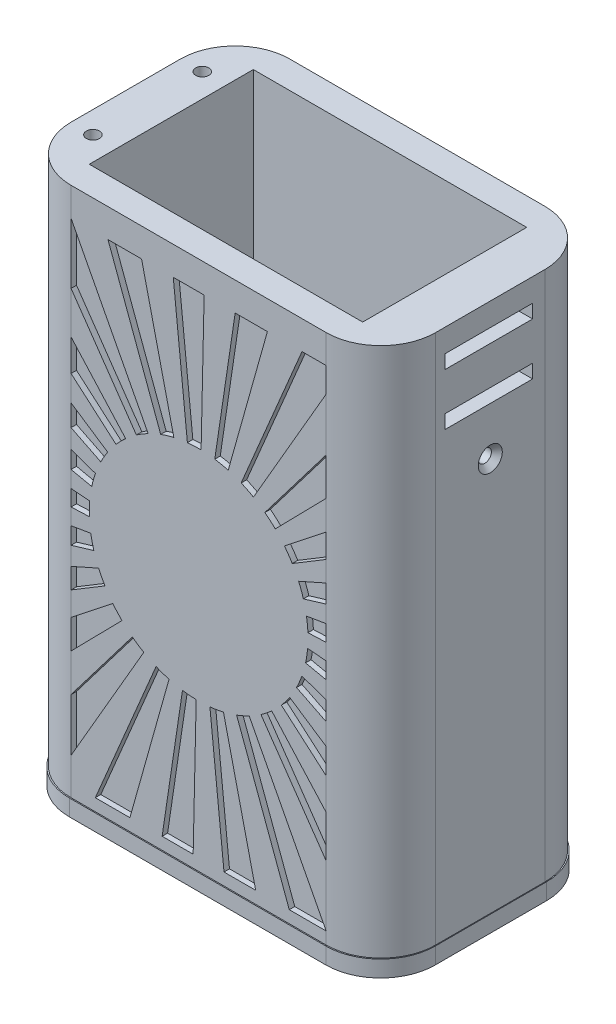
SolidWorks part; units mm, degrees
ref_plane "Front Plane" through (0, 0, 0) normal (0, 0, 1) x (1, 0, 0)
ref_plane "Top Plane" through (0, 0, 0) normal (0, 1, 0) x (1, 0, 0)
ref_plane "Right Plane" through (0, 0, 0) normal (1, 0, 0) x (0, 0, -1)
sketch "Sketch4" plane through (0, 0, 0) normal (0, 1, 0) x (1, 0, 0)
  line L1 (23.3333, 20) -> (-23.3333, 20)
  line L2 (33.3333, 10) -> (33.3333, -10)
  line L3 (23.3333, -20) -> (-23.3333, -20)
  line L4 (-33.3333, 10) -> (-33.3333, -10)
  line L5 (33.3333, 20) -> (-33.3333, -20) construction
  line L6 (33.3333, -20) -> (-33.3333, 20) construction
  line L7 (25, 15) -> (-25, 15)
  line L8 (25, 15) -> (25, -15)
  line L9 (25, -15) -> (-25, -15)
  line L10 (-25, 15) -> (-25, -15)
  line L11 (25, 15) -> (-25, -15) construction
  line L12 (25, -15) -> (-25, 15) construction
  arc A0 (23.3333, 20) -> (33.3333, 10) centre (23.3333, 10) cw
  arc A1 (-23.3333, -20) -> (-33.3333, -10) centre (-23.3333, -10) cw
  arc A2 (33.3333, -10) -> (23.3333, -20) centre (23.3333, -10) cw
  arc A3 (-23.3333, 20) -> (-33.3333, 10) centre (-23.3333, 10) ccw
  point P0 (0, 0)
  point P18 (0, 0)
  dimension "D1" = 10
extrude "Boss-Extrude1" add sketch "Sketch4" along normal blind 100
sketch "Sketch6" plane through (0, 0, 20) normal (0, 0, 1) x (1, 0, 0)
  line L0 (0, -22) -> (0, 22) construction
  line L1 (-23.3333, 94.7801) -> (23.3333, 94.7801)
  line L2 (-23.3333, 94.7801) -> (-23.3333, 5.2199)
  line L3 (-23.3333, 5.2199) -> (23.3333, 5.2199)
  line L4 (23.3333, 94.7801) -> (23.3333, 5.2199)
  line L5 (-23.3333, 94.7801) -> (-9.2335, 67.7204) construction
  line L6 (-23.3333, 5.2199) -> (-9.2498, 32.2482) construction
  line L7 (23.3333, 100) -> (23.3333, 0) construction
  line L8 (22, 0) -> (-22, 0) construction
  line L9 (-9.2335, 67.7204) -> (-23.3333, 94.7801)
  line L10 (0.0013, 49.9999) -> (0.0007, 50.0014)
  line L11 (0.0025, 49.9997) -> (0.0017, 50.0032)
  line L12 (0.0037, 49.9993) -> (0.003, 50.0058)
  line L13 (0.0048, 49.9988) -> (0.0051, 50.0097)
  line L14 (0.0059, 49.9981) -> (0.0086, 50.0166)
  line L15 (0.0068, 49.9973) -> (0.0165, 50.0316)
  line L16 (0.0077, 49.9964) -> (0.0486, 50.0932)
  line L17 (10.0235, 67.2878) -> (23.3333, 90.2692)
  line L18 (12.1129, 65.8957) -> (23.3333, 80.6366)
  line L19 (14.0116, 64.2528) -> (23.3333, 73.7462)
  line L20 (15.6895, 62.3849) -> (23.3333, 68.4265)
  line L21 (17.1202, 60.3213) -> (23.3333, 64.0726)
  line L22 (18.2811, 58.0946) -> (23.3333, 60.3358)
  line L23 (19.1539, 55.7398) -> (23.3333, 56.9955)
  line L24 (19.7248, 53.294) -> (23.3333, 53.8994)
  line L25 (19.9846, 50.7959) -> (23.3333, 50.9317)
  line L26 (19.9293, 48.2847) -> (23.3333, 47.9942)
  line L27 (0.0077, 49.9836) -> (0.0086, 49.9834)
  line L28 (0.0068, 49.9827) -> (0.0095, 49.9818)
  line L29 (0.0059, 49.9819) -> (0.0107, 49.9795)
  line L30 (0.0048, 49.9812) -> (0.0124, 49.9762)
  line L31 (0.0037, 49.9807) -> (0.0153, 49.9707)
  line L32 (-0.0525, 50.0416) -> (0.021, 49.9597)
  line L33 (0.0013, 49.9801) -> (0.038, 49.927)
  line L34 (9.2422, 32.2429) -> (23.3333, 5.1999)
  line L35 (6.9451, 31.2242) -> (16.576, 5.2199)
  line L36 (4.5384, 30.5015) -> (10.4321, 5.2199)
  line L37 (2.0601, 30.0863) -> (4.6396, 5.2199)
  line L38 (-0.4508, 29.9852) -> (-1.0031, 5.2199)
  line L39 (-2.9544, 30.1997) -> (-6.6777, 5.2199)
  line L40 (-5.4114, 30.7264) -> (-12.5702, 5.2199)
  line L41 (-7.7829, 31.5571) -> (-18.896, 5.2199)
  line L42 (-10.0314, 32.6785) -> (-23.3333, 9.7108)
  line L43 (-12.1215, 34.0729) -> (-23.3333, 19.3434)
  line L44 (-14.0202, 35.7183) -> (-23.3333, 26.2338)
  line L45 (-15.6976, 37.5887) -> (-23.3333, 31.5535)
  line L46 (-17.1272, 39.6545) -> (-23.3333, 35.9074)
  line L47 (-18.2864, 41.8831) -> (-23.3333, 39.6442)
  line L48 (-19.1571, 44.2392) -> (-23.3333, 42.9845)
  line L49 (-19.7256, 46.6858) -> (-23.3333, 46.0806)
  line L50 (-0.009, 49.9943) -> (-0.01, 49.9942)
  line L51 (-0.0084, 49.9954) -> (-0.0112, 49.9956)
  line L52 (-0.0077, 49.9964) -> (-0.0129, 49.9975)
  line L53 (-0.0068, 49.9973) -> (-0.0155, 50.0003)
  line L54 (-0.0059, 49.9981) -> (-0.0196, 50.0049)
  line L55 (-0.0048, 49.9988) -> (-0.0279, 50.0141)
  line L56 (-0.0037, 49.9993) -> (-0.0525, 50.0416)
  line L57 (-13.3535, 64.868) -> (-23.3333, 75.9819)
  line L58 (-11.3832, 66.4238) -> (-23.3333, 83.6676)
  line L59 (-23.3333, 94.7801) -> (-23.3333, 5.2199)
  line L60 (23.3333, 94.7801) -> (23.3333, 5.2199)
  line L61 (9.2503, 32.2472) -> (23.3333, 5.2199) construction
  line L62 (-0.0056, 49.9893) -> (0.0486, 50.0932) construction
  line L63 (-19.9829, 49.1842) -> (-23.3333, 49.0483)
  line L64 (-19.9251, 51.695) -> (-23.3333, 51.9858)
  line L65 (-19.5531, 54.1785) -> (-23.3333, 54.9874)
  line L66 (-18.8729, 56.5958) -> (-23.3333, 58.1559)
  line L67 (-17.8952, 58.9086) -> (-23.3333, 61.6173)
  line L68 (-16.6354, 61.0806) -> (-23.3333, 65.5438)
  line L69 (-15.1135, 63.0775) -> (-23.3333, 70.1921)
  line L70 (0, 50) -> (0.038, 49.927) construction
  line L71 (-6.9383, 68.7375) -> (-16.5834, 94.7801)
  line L72 (-4.5339, 69.4591) -> (-10.4367, 94.7801)
  line L73 (-2.058, 69.8738) -> (-4.6417, 94.7801)
  line L74 (0.4503, 69.975) -> (1.0035, 94.7801)
  line L75 (2.9516, 69.7613) -> (6.6807, 94.7801)
  line L76 (5.4064, 69.2358) -> (12.5758, 94.7801)
  line L77 (7.7762, 68.407) -> (18.9044, 94.7801)
  line L78 (9.234, 67.7214) -> (23.3333, 94.7801) construction
  line L79 (19.5596, 45.8001) -> (23.3333, 44.9926)
  line L80 (18.8813, 43.3813) -> (23.3333, 41.8241)
  line L81 (17.9051, 41.0664) -> (23.3333, 38.3627)
  line L82 (16.6463, 38.8922) -> (23.3333, 34.4362)
  line L83 (15.1248, 36.8927) -> (23.3333, 29.7879)
  line L84 (13.3645, 35.0998) -> (23.3333, 23.9981)
  line L85 (11.3933, 33.5417) -> (23.3333, 16.3124)
  circle A0 centre (0.0013, 49.9801) radius 20
  point P0 (0, 50)
  dimension "D1" = 50
  dimension "D2" = 50
hole_wizard "CSK for M2 Countersunk Flat Head Screw1" positions "Sketch8" profile "Sketch7" countersink size "M2" standard "ISO"
sketch "Sketch8" plane through (33.3333, 0, 0) normal (1, 0, 0) x (0, 0, -1)
  line L0 (-10, 100) -> (10, 100) construction
  point P1 (0, 75)
  dimension "D1" = 25
sketch "Sketch7" plane through (33.3333, 75, 0) normal (0, 1, 0) x (0, 0, -1)
  line L0 (0, 0) -> (0, 20.721)
  line L1 (0, 20.721) -> (1.2, 20)
  line L2 (1.2, 20) -> (1.2, 1)
  line L3 (1.2, 1) -> (2.2, 0)
  line L5 (2.2, 0) -> (0, 0)
  line L6 (-1.2, 1) -> (-2.2, 0) construction
  line L10 (0, 20.721) -> (-1.2, 20) construction
  line L11 (0, -6.35) -> (0, 107.95) construction
  dimension "Hole Dia." = 2.4
  dimension "Hole Depth" = 20
  dimension "Near C'Sink Dia." = 4.4
  dimension "Near C'Sink Angle" = 90
  dimension "Drill Angle" = 118
sketch "Sketch9" plane through (33.3333, 0, 0) normal (1, 0, 0) x (0, 0, -1)
  line L0 (-8.256, 93.2854) -> (7.744, 93.2854)
  line L1 (-8.256, 95.7854) -> (7.744, 95.7854)
  line L2 (-8.256, 95.7854) -> (-8.256, 93.2854)
  line L3 (-8.256, 83.7854) -> (7.744, 83.7854)
  line L4 (7.744, 95.7854) -> (7.744, 93.2854)
  line L5 (-8.256, 95.7854) -> (-4.9227, 93.2854) construction
  line L6 (-8.256, 83.7854) -> (-4.9227, 86.2854) construction
  line L7 (-8.256, 86.2854) -> (7.744, 86.2854)
  line L8 (7.744, 86.2854) -> (7.744, 83.7854)
  line L9 (4.4107, 86.2854) -> (7.744, 83.7854) construction
  line L10 (4.4107, 93.2854) -> (7.744, 95.7854) construction
  line L11 (-8.256, 86.2854) -> (-8.256, 83.7854)
  point P0 (-0.256, 89.7854)
  dimension "D1" = 2.5
  dimension "D2" = 2.5
extrude "Cut-Extrude3" cut sketch "Sketch6" against normal blind 1 contours A0 L9 L57 L58 | A0 L72 L1 L71 | A0 L74 L1 L73 | A0 L76 L1 L75 | A0 L17 L4 L1 L77 | A0 L19 L4 L18 | A0 L21 L4 L20 | A0 L23 L4 L22 | A0 L25 L4 L24 | A0 L79 L60 L26 | A0 L81 L60 L80 | A0 L83 L60 L82 | A0 L85 L60 L84 | A0 L35 L3 L34 | A0 L37 L3 L36 | A0 L39 L3 L38 | A0 L41 L3 L40 | A0 L43 L2 L42 | A0 L45 L2 L44 | A0 L47 L2 L46 | A0 L49 L2 L48 | A0 L66 L59 L65 | A0 L68 L59 L67 | A0 L57 L2 L69 | A0 L64 L59 L63
mirror "Mirror1" about plane through (0, 0, 0) normal (0, 0, 1) of "Cut-Extrude3"
hole_wizard "M2 Clearance Hole1" positions "Sketch10" profile "Sketch11" hole size "M2" standard "ISO"
sketch "Sketch10" plane through (0, 100, 0) normal (0, 1, 0) x (1, 0, 0)
  line L0 (-25, -15) -> (25, -15) construction
  line L1 (25, 15) -> (-25, 15) construction
  line L2 (-33.3333, 10) -> (-33.3333, -10) construction
  point P0 (-29.3333, -10)
  point P2 (-29.3333, 10)
  dimension "D1" = 5
  dimension "D2" = 5
  dimension "D3" = 4
  dimension "D4" = 4
sketch "Sketch11" plane through (-29.3333, 100, 10) normal (1, 0, 0) x (0, 0, 1)
  line L0 (0, 0) -> (0, 10.721)
  line L1 (0, 10.721) -> (1.2, 10)
  line L2 (1.2, 10) -> (1.2, 0)
  line L5 (1.2, 0) -> (0, 0)
  line L10 (0, 10.721) -> (-1.2, 10) construction
  line L11 (0, -6.35) -> (0, 107.95) construction
  dimension "Hole Dia." = 2.4
  dimension "Hole Depth" = 10
  dimension "Drill Angle" = 118
extrude "Cut-Extrude4" cut sketch "Sketch9" against normal blind 10
ref_plane "Plane1" through (-23.3333, 0, -20) normal (-1, 0, 0) x (0, 0, 1)
sketch "Sketch13" plane through (0, 0, 0) normal (0, -1, 0) x (-1, 0, 0)
  line L1 (23.4637, 20.191) -> (-23.4637, 20.191)
  line L2 (33.4637, 10.191) -> (33.4637, -10.191)
  line L3 (23.4637, -20.191) -> (-23.4637, -20.191)
  line L4 (-33.4637, 10.191) -> (-33.4637, -10.191)
  line L5 (33.4637, 20.191) -> (-33.4637, -20.191) construction
  line L6 (33.4637, -20.191) -> (-33.4637, 20.191) construction
  arc A0 (-23.4637, 20.191) -> (-33.4637, 10.191) centre (-23.4637, 10.191) ccw
  arc A1 (-23.4637, -20.191) -> (-33.4637, -10.191) centre (-23.4637, -10.191) cw
  arc A2 (33.4637, -10.191) -> (23.4637, -20.191) centre (23.4637, -10.191) cw
  arc A3 (23.4637, 20.191) -> (33.4637, 10.191) centre (23.4637, 10.191) cw
  point P0 (0, 0)
  dimension "D1" = 10
extrude "Boss-Extrude2" add sketch "Sketch13" against normal blind 3
sketch "Sketch14" plane through (0, 0, 0) normal (0, -1, 0) x (1, 0, 0)
  line L1 (-7, -4.5) -> (7, -4.5)
  line L2 (-7, -4.5) -> (-7, 4.5)
  line L3 (-7, 4.5) -> (7, 4.5)
  line L4 (7, -4.5) -> (7, 4.5)
  line L5 (-7, -4.5) -> (7, 4.5) construction
  line L6 (-7, 4.5) -> (7, -4.5) construction
  point P0 (0, 0)
extrude "Cut-Extrude5" cut sketch "Sketch14" against normal blind 3
